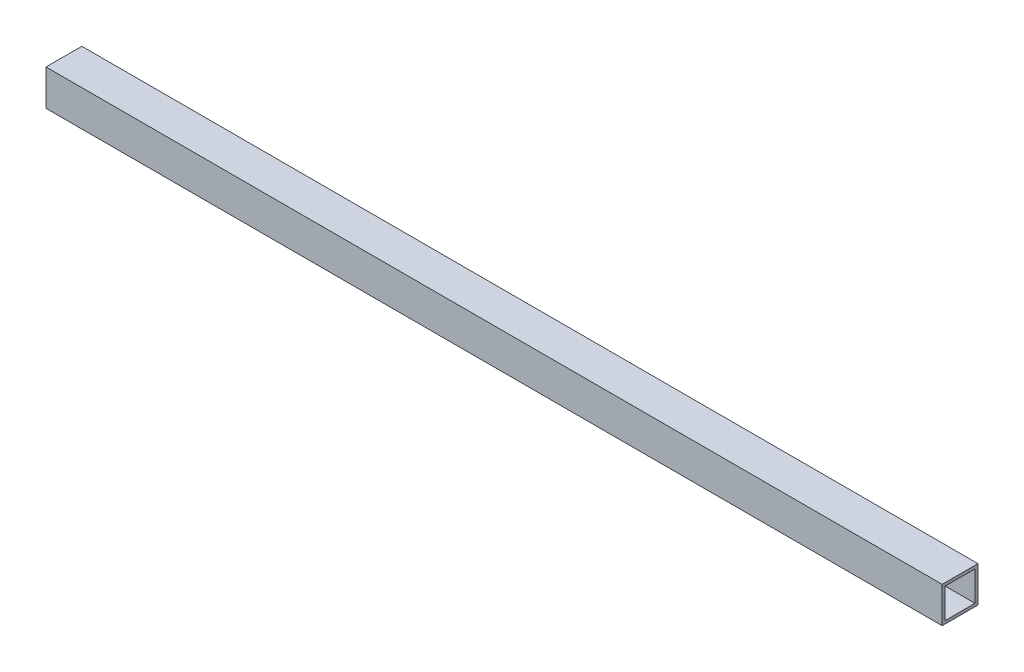
SolidWorks part; units mm, degrees
ref_plane "前视基准面" through (0, 0, 0) normal (0, 0, 1) x (1, 0, 0)
ref_plane "上视基准面" through (0, 0, 0) normal (0, 1, 0) x (1, 0, 0)
ref_plane "右视基准面" through (0, 0, 0) normal (1, 0, 0) x (0, 0, -1)
other "Configuration Table"
sketch "草图2" plane through (0, 0, 0) normal (1, 0, 0) x (0, 0, -1)
  line L0 (-12, -12) -> (-12, 12)
  line L1 (-10, -10) -> (10, -10)
  line L2 (-10, -10) -> (-10, 10)
  line L3 (-10, 10) -> (10, 10)
  line L4 (10, -10) -> (10, 10)
  line L5 (-10, -10) -> (10, 10) construction
  line L6 (-10, 10) -> (10, -10) construction
  line L7 (-12, 12) -> (12, 12)
  line L8 (12, -12) -> (12, 12)
  line L9 (-12, -12) -> (12, -12)
  point P0 (0, 0)
  dimension "D1" = 20
  dimension "D3" = 20
  dimension "D2" = 2
extrude "凸台-拉伸3" add sketch "草图2" along normal blind 600
equation "\"a\"= 20'mm"
equation "\"D1@草图2\"=\"a\""
equation "\"D3@草图2\"=\"a\""
equation "\"b\" = 600'mm"
equation "\"D1@凸台-拉伸3\"= \"b\""
